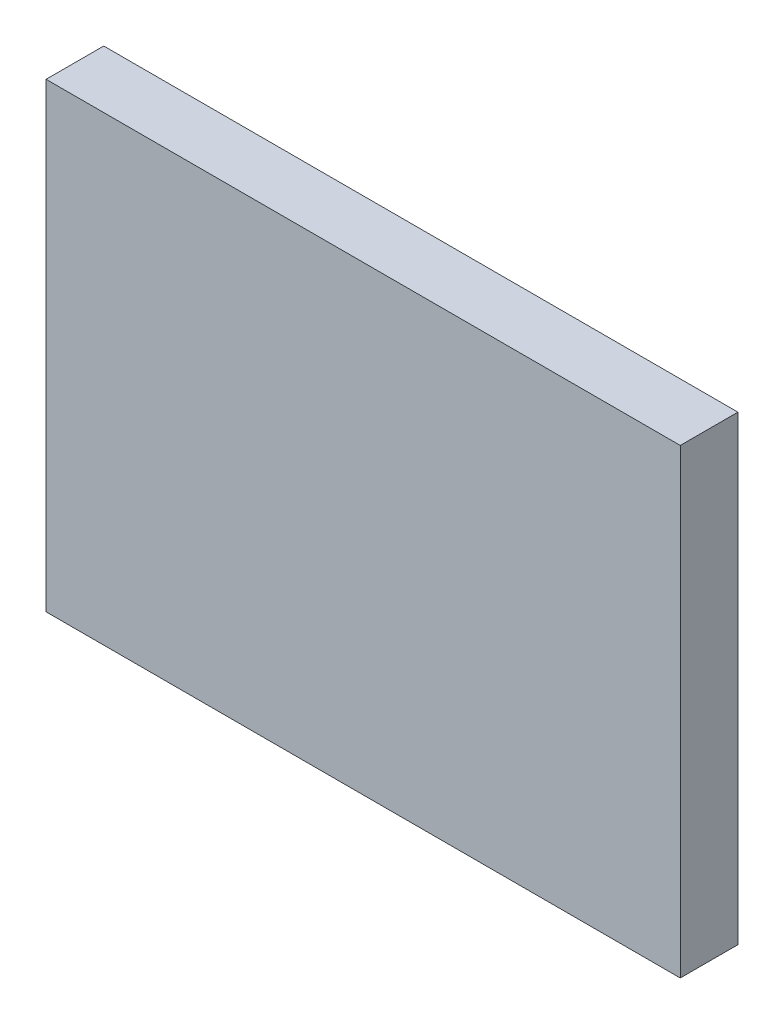
SolidWorks part; units mm, degrees
ref_plane "Front Plane" through (0, 0, 0) normal (0, 0, 1) x (1, 0, 0)
ref_plane "Top Plane" through (0, 0, 0) normal (0, 1, 0) x (1, 0, 0)
ref_plane "Right Plane" through (0, 0, 0) normal (1, 0, 0) x (0, 0, -1)
sketch "Sketch1" plane through (0, 0, 0) normal (0, 0, 1) x (1, 0, 0)
  line L1 (0, 0) -> (69.85, 0)
  line L2 (0, 0) -> (0, 50.8)
  line L3 (0, 50.8) -> (69.85, 50.8)
  line L4 (69.85, 0) -> (69.85, 50.8)
  dimension "D1" = 69.85
  dimension "D2" = 50.8
extrude "Boss-Extrude1" add sketch "Sketch1" along normal blind 6.35
